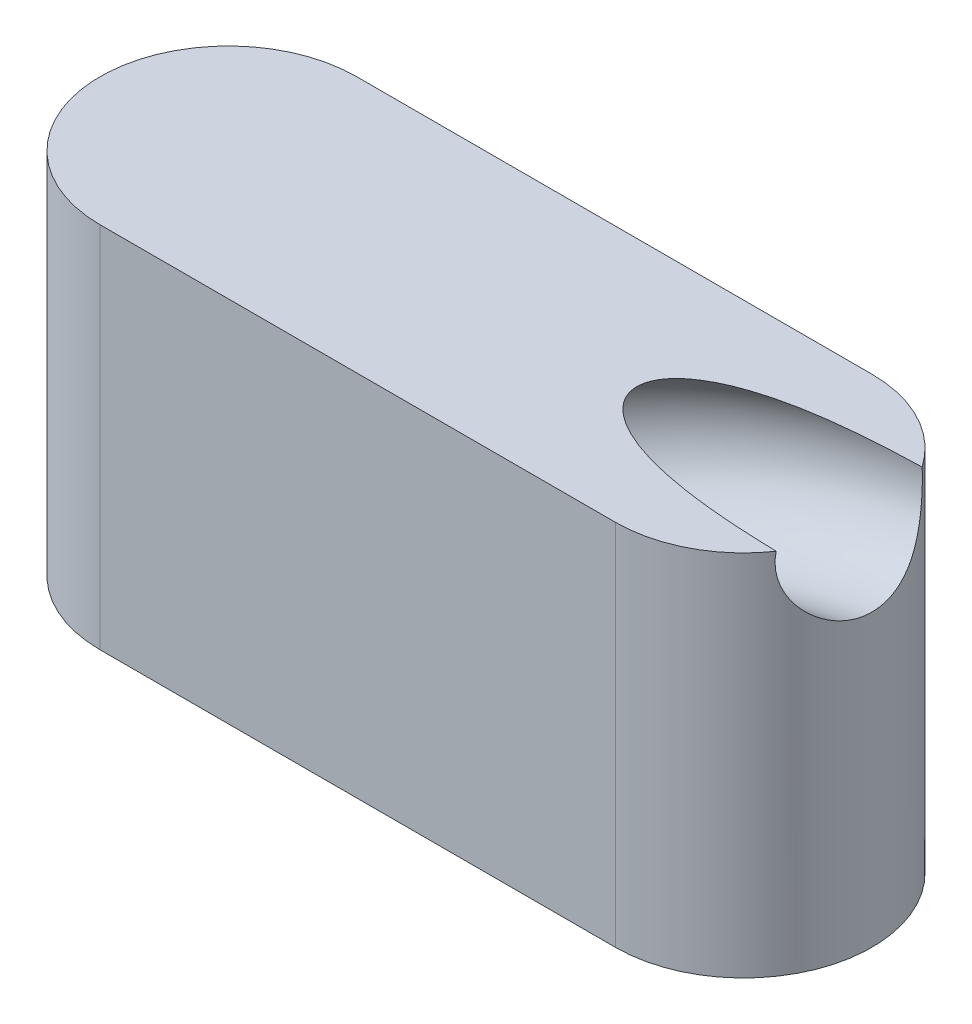
SolidWorks part; units mm, degrees
ref_plane "Front Plane" through (0, 0, 0) normal (0, 0, 1) x (1, 0, 0)
ref_plane "Top Plane" through (0, 0, 0) normal (0, 1, 0) x (1, 0, 0)
ref_plane "Right Plane" through (0, 0, 0) normal (1, 0, 0) x (0, 0, -1)
sketch "Sketch1" plane through (0, 0, 0) normal (0, 1, 0) x (1, 0, 0)
  line L0 (-1.0372, 0) -> (0.3628, 0) construction
  line L1 (-1.0372, 0.3484) -> (0.3628, 0.3484)
  line L2 (-1.0372, -0.3484) -> (0.3628, -0.3484)
  arc A0 (-1.0372, 0.3484) -> (-1.0372, -0.3484) centre (-1.0372, 0) ccw
  arc A1 (0.3628, -0.3484) -> (0.3628, 0.3484) centre (0.3628, 0) ccw
  point P3 (-0.3372, 0)
  dimension "D1" = 0.3484
  dimension "D2" = 1.4
extrude "Boss-Extrude1" add sketch "Sketch1" along normal blind 1
sketch "Sketch2" plane through (0, 0, 0) normal (0, 0, 1) x (1, 0, 0)
  line L0 (-1.3856, 0) -> (-1.0372, 0) construction
  line L1 (-1.3856, 0) -> (-1.0372, 0) construction
  line L2 (0.7112, 1) -> (0.3628, 1) construction
  line L3 (0.8136, 1) -> (0.3628, 1) construction
  circle A0 centre (-2.0113, 2.4325) radius 2.5116 construction
  circle A1 centre (1.1191, -1.4813) radius 2.5 construction
  arc A2 (-0.4459, 0.4683) -> (-1.3856, 0) centre (-2.0113, 2.4325) cw
  arc A3 (-0.4459, 0.4683) -> (0.8136, 1) centre (1.1318, -1.5115) cw
  dimension "D1" = 5
ref_plane "Plane1" through (-1.3856, 1, 0) normal (-1, 0, 0) x (0, 0, 1)
sketch "Sketch4" plane through (-1.3856, 1, 0) normal (-1, 0, 0) x (0, 0, 1)
  circle A0 centre (0, -1) radius 0.2
  dimension "D1" = 0.4
sweep "Cut-Sweep3" cut profiles "Sketch4" path "Sketch2"
